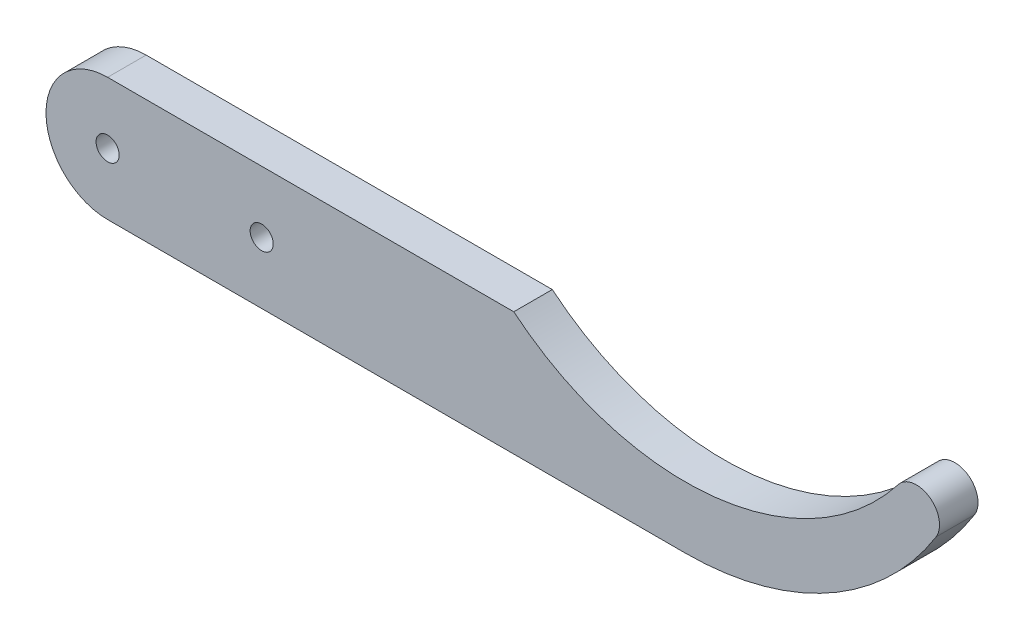
SolidWorks part; units mm, degrees
ref_plane "Plan de face" through (0, 0, 0) normal (0, 0, 1) x (1, 0, 0)
ref_plane "Plan de dessus" through (0, 0, 0) normal (0, 1, 0) x (1, 0, 0)
ref_plane "Plan de droite" through (0, 0, 0) normal (1, 0, 0) x (0, 0, -1)
sketch "Esquisse1" plane through (0, 0, 0) normal (0, 0, 1) x (1, 0, 0)
  line L0 (0, 0) -> (80, 0) construction
  line L1 (20, 0) -> (20, 23.8674) construction
  line L2 (0, 0) -> (0, 35) construction
  line L3 (0, 35) -> (55, 35) construction
  line L4 (0, 8) -> (20, 8)
  line L5 (82.6316, 13.5175) -> (85, 11.6762) construction
  line L6 (20, 8) -> (32.7289, 8)
  line L7 (0, -8) -> (55, -8)
  line L8 (55, 35) -> (55, -8) construction
  line L9 (0, 8) -> (-20, 8)
  line L10 (0, 0) -> (-20, 0) construction
  line L11 (0, -8) -> (-20, -8)
  circle A0 centre (0, 0) radius 1.5
  arc A1 (0, 8) -> (0, -8) centre (0, 0) ccw construction
  circle A2 centre (55, 35) radius 35 construction
  arc A3 (32.7289, 8) -> (82.6316, 13.5175) centre (55, 35) ccw
  arc A4 (82.6316, 13.5175) -> (87.5479, 10.0925) centre (85, 11.6762) cw
  arc A5 (55, -8) -> (87.5479, 10.0925) centre (55, 30.3227) ccw
  circle A6 centre (15, 0) radius 1.5 construction
  arc A7 (-20, 8) -> (-20, -8) centre (-20, 0) ccw
  circle A8 centre (-20, 0) radius 1.5
  dimension "D3" = 3
  dimension "D4" = 35
  dimension "D6" = 70
  dimension "D7" = 3
  dimension "D8" = 8
  dimension "D9" = 30
  dimension "D10" = 15
  dimension "D11" = 8
  dimension "D1" = 20
  dimension "D2" = 80
  dimension "D5" = 55
  dimension "D12" = 20
extrude "Boss.-Extru.1" add sketch "Esquisse1" along normal blind 5
